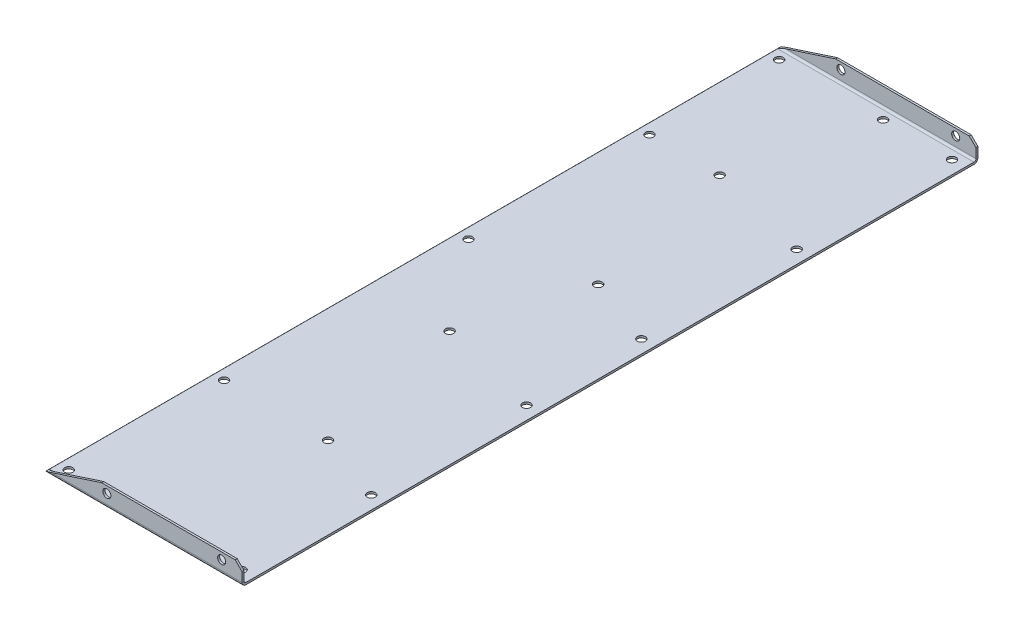
SolidWorks part; units mm, degrees
material "1.4541 (X6CrNiTi18-10)"
ref_plane "Piano frontale" through (0, 0, 0) normal (0, 0, 1) x (1, 0, 0)
ref_plane "Piano superiore" through (0, 0, 0) normal (0, 1, 0) x (1, 0, 0)
ref_plane "Piano destro" through (0, 0, 0) normal (1, 0, 0) x (0, 0, -1)
sketch "Schizzo1" plane through (0, 0, 0) normal (1, 0, 0) x (0, 0, -1)
  line L1 (-269.5, 0) -> (269.5, 0)
  line L2 (-272.5, 3) -> (-272.5, 15)
  line L4 (272.5, 3) -> (272.5, 15)
  arc A0 (-269.5, 0) -> (-272.5, 3) centre (-269.5, 3) cw
  arc A1 (269.5, 0) -> (272.5, 3) centre (269.5, 3) ccw
  point P7 (-272.5, 0)
  point P10 (272.5, 0)
  dimension "D3" = 3
  dimension "D1" = 545
  dimension "D2" = 15
extrude "Estrusione-Sottile1" add sketch "Schizzo1" along normal blind 150 thin thin type one direction wall 1.5
sketch "Schizzo2" plane through (0, 0, 272.5) normal (0, 0, 1) x (1, 0, 0)
  line L0 (166.852, 10) -> (-11.5555, 10) construction
  line L1 (150, 15) -> (0, 15) construction
  line L2 (150, 3) -> (150, 15) construction
  line L3 (0, 3) -> (0, 15) construction
  circle A0 centre (135, 10) radius 3
  circle A1 centre (50, 10) radius 3
  dimension "D4" = 6
  dimension "D5" = 6
  dimension "D1" = 5
  dimension "D2" = 15
  dimension "D3" = 50
extrude "Taglio-Estrusione1" cut sketch "Schizzo2" against normal through all
sketch "Schizzo3" plane through (0, 0, 272.5) normal (0, 0, 1) x (1, 0, 0)
  line L0 (4.5, 1.4621) -> (46.1653, 15)
  line L1 (150, 15) -> (0, 15) construction
  line L2 (4.5, 1.4621) -> (4.5, 0)
  line L3 (150, 0) -> (0, 0) construction
  line L4 (0, 0) -> (0, 15)
  line L5 (0, 15) -> (46.1653, 15)
  line L6 (4.5, 0) -> (0, 0)
  dimension "D1" = 18
  dimension "D2" = 4.5
extrude "Taglio-Estrusione2" cut sketch "Schizzo3" against normal through all
sketch "Schizzo4" plane through (0, 1.5, 0) normal (0, 1, 0) x (1, 0, 0)
  circle A6 centre (12.2459, 33) radius 3 construction
  circle A7 centre (12.2459, 167) radius 3 construction
  circle A8 centre (12.2459, 263) radius 3 construction
  circle A14 centre (12.2459, -263) radius 3 construction
  circle A18 centre (12.2459, -148) radius 3 construction
  circle A19 centre (12.2459, 33) radius 3
  circle A20 centre (12.2459, 167) radius 3
  circle A21 centre (12.2459, 263) radius 3
  circle A22 centre (12.2459, -263) radius 3
  circle A23 centre (12.2459, -148) radius 3
  circle A24 centre (64.2459, 167) radius 3 construction
  circle A25 centre (89.2459, 52) radius 3 construction
  circle A26 centre (64.2459, -33) radius 3 construction
  circle A27 centre (89.2459, -148) radius 3 construction
  circle A29 centre (64.2459, -263) radius 3 construction
  circle A30 centre (64.2459, 167) radius 3
  circle A31 centre (89.2459, 52) radius 3
  circle A32 centre (64.2459, -33) radius 3
  circle A33 centre (89.2459, -148) radius 3
  circle A34 centre (64.2459, -263) radius 3
  circle A35 centre (140.2459, -167) radius 3 construction
  circle A36 centre (140.2459, -52) radius 3 construction
  circle A37 centre (140.2459, 33) radius 3 construction
  circle A38 centre (140.2459, 148) radius 3 construction
  circle A39 centre (89.2459, 263) radius 3 construction
  circle A40 centre (140.2459, -167) radius 3
  circle A41 centre (140.2459, -52) radius 3
  circle A42 centre (140.2459, 33) radius 3
  circle A43 centre (140.2459, 148) radius 3
  circle A44 centre (89.2459, 263) radius 3
  circle A45 centre (140.2459, 263) radius 3 construction
  circle A46 centre (140.2459, -263) radius 3 construction
  circle A47 centre (140.2459, 263) radius 3
  circle A48 centre (140.2459, -263) radius 3
extrude "Taglio-Estrusione3" cut sketch "Schizzo4" against normal blind 10
chamfer "Smusso1" distance 5 angle 45 2 edges at (150, 15, 271.75) (150, 15, -271.75)
